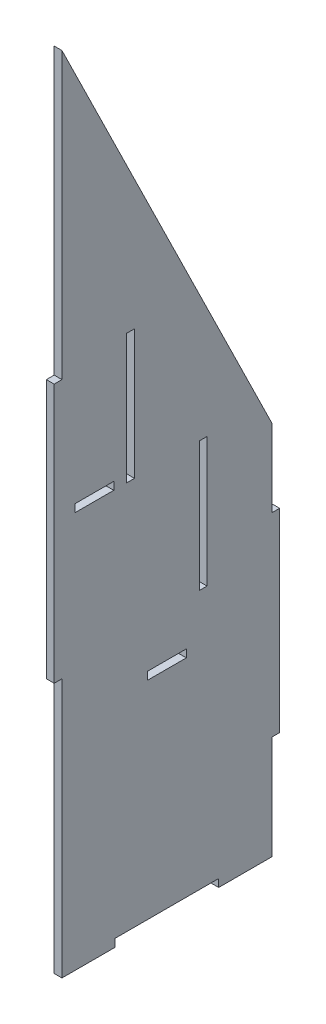
SolidWorks part; units mm, degrees
ref_plane "Alzado" through (0, 0, 0) normal (0, 0, 1) x (1, 0, 0)
ref_plane "Planta" through (0, 0, 0) normal (0, 1, 0) x (1, 0, 0)
ref_plane "Vista lateral" through (0, 0, 0) normal (1, 0, 0) x (0, 0, -1)
sketch "Croquis1" plane through (0, 0, 0) normal (1, 0, 0) x (0, 0, -1)
  line L0 (0, 0) -> (0, 100)
  line L1 (0, 310) -> (81, 145)
  line L2 (81, 145) -> (81, 115)
  line L3 (81, 0) -> (60.5, 0)
  line L4 (0, 200) -> (0, 310)
  line L5 (0, 200) -> (-3, 200)
  line L7 (0, 100) -> (-3, 100)
  line L8 (-3, 200) -> (-3, 100)
  line L9 (81, 115) -> (84, 115)
  line L11 (81, 40) -> (84, 40)
  line L12 (84, 115) -> (84, 40)
  line L14 (20.5, 0) -> (20.5, 3)
  line L15 (20.5, 3) -> (60.5, 3)
  line L16 (60.5, 0) -> (60.5, 3)
  line L17 (81, 40) -> (81, 0)
  line L18 (20.5, 0) -> (0, 0)
  dimension "D1" = 310
  dimension "D2" = 145
  dimension "D3" = 81
  dimension "D4" = 100
  dimension "D5" = 100
  dimension "D6" = 3
  dimension "D7" = 75
  dimension "D8" = 40
  dimension "D9" = 3
  dimension "D10" = 40
  dimension "D11" = 20.5
  dimension "D12" = 3
extrude "Saliente-Extruir1" add sketch "Croquis1" along normal blind 3
sketch "Croquis2" plane through (3, 0, 0) normal (1, 0, 0) x (0, 0, -1)
  line L1 (25, 203) -> (28, 203)
  line L2 (25, 203) -> (25, 153)
  line L3 (25, 153) -> (28, 153)
  line L4 (28, 203) -> (28, 153)
  line L5 (53, 153) -> (56, 153)
  line L6 (53, 153) -> (53, 103)
  line L7 (53, 103) -> (56, 103)
  line L8 (56, 153) -> (56, 103)
  line L9 (20.5, 3) -> (60.5, 3) construction
  line L10 (0, 310) -> (0, 200) construction
  line L11 (0, 100) -> (0, 0) construction
  dimension "D1" = 50
  dimension "D2" = 50
  dimension "D3" = 100
  dimension "D4" = 150
  dimension "D5" = 25
  dimension "D6" = 53
  dimension "D7" = 3
  dimension "D8" = 3
extrude "Cortar-Extruir2" cut sketch "Croquis2" against normal blind 70
sketch "Croquis4" plane through (3, 0, 0) normal (1, 0, 0) x (0, 0, -1)
  line L0 (25, 153) -> (25, 203) construction
  line L1 (28, 153) -> (28, 203) construction
  line L2 (20.5, 3) -> (60.5, 3) construction
  line L3 (5, 156) -> (20, 156)
  line L5 (5, 153) -> (20, 153)
  line L6 (20, 156) -> (20, 153)
  line L7 (33, 86) -> (48, 86)
  line L8 (33, 86) -> (33, 83)
  line L9 (33, 83) -> (48, 83)
  line L10 (48, 86) -> (48, 83)
  line L11 (5, 153) -> (5, 156)
  dimension "D1" = 15
  dimension "D2" = 15
  dimension "D3" = 80
  dimension "D4" = 150
  dimension "D5" = 5
  dimension "D6" = 5
  dimension "D7" = 3
  dimension "D8" = 3
extrude "Cortar-Extruir3" cut sketch "Croquis4" against normal blind 3
